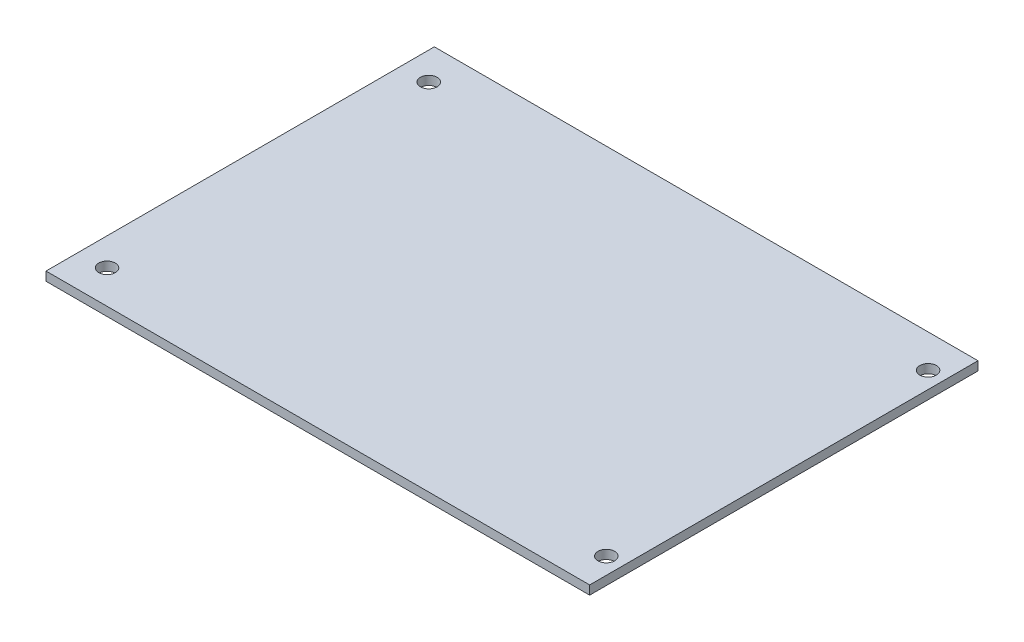
SolidWorks part; units mm, degrees
ref_plane "Спереди" through (0, 0, 0) normal (0, 0, 1) x (1, 0, 0)
ref_plane "Сверху" through (0, 0, 0) normal (0, 1, 0) x (1, 0, 0)
ref_plane "Справа" through (0, 0, 0) normal (1, 0, 0) x (0, 0, -1)
sketch "Эскиз1" plane through (0, 0, 0) normal (0, 1, 0) x (1, 0, 0)
  line L0 (-49, 0) -> (49, 0) construction
  line L1 (-49, -35) -> (49, -35)
  line L2 (-49, -35) -> (-49, 35)
  line L3 (-49, 35) -> (49, 35)
  line L4 (49, -35) -> (49, 35)
  line L5 (-49, -35) -> (49, 35) construction
  line L6 (-49, 35) -> (49, -35) construction
  line L7 (41, 0) -> (139, 0) construction
  circle A0 centre (-44, 29) radius 1.5
  circle A1 centre (-44, -29) radius 1.5
  circle A2 centre (46, 29) radius 1.5
  circle A3 centre (46, -29) radius 1.5
  point P0 (0, 0)
  dimension "D3" = 3
  dimension "D1" = 98
  dimension "D2" = 70
  dimension "D4" = 58
  dimension "D5" = 5
  dimension "D6" = 2
extrude "Бобышка-Вытянуть1" add sketch "Эскиз1" along normal blind 1.6
